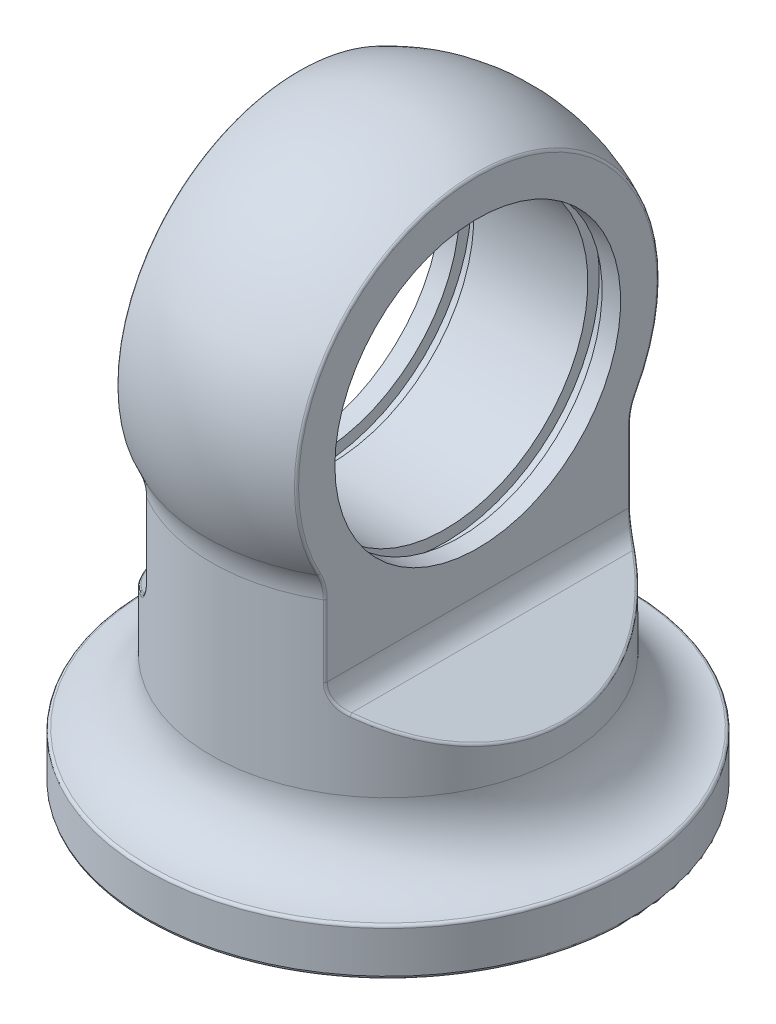
SolidWorks part; units mm, degrees
material "6061-T6 (SS)"
ref_plane "Front Plane" through (0, 0, 0) normal (0, 0, 1) x (1, 0, 0)
ref_plane "Top Plane" through (0, 0, 0) normal (0, 1, 0) x (1, 0, 0)
ref_plane "Right Plane" through (0, 0, 0) normal (1, 0, 0) x (0, 0, -1)
sketch "Sketch11" plane through (0, 0, 0) normal (0, 0, 1) x (1, 0, 0)
  line L0 (0, -7.7453) -> (0, 14.6095) construction
  line L1 (0, 20.32) -> (6.985, 16.123)
  line L2 (6.985, 16.123) -> (6.985, 0)
  line L3 (6.985, 0) -> (21.5138, 0)
  line L4 (21.5138, 0) -> (21.5138, 4.191)
  line L5 (15.748, 9.9568) -> (15.748, 24.8596)
  line L6 (0, 52.832) -> (0, 20.32)
  arc A0 (21.5138, 4.191) -> (15.748, 9.9568) centre (21.5138, 9.9568) cw
  arc A1 (15.748, 24.8596) -> (16.2454, 27.0518) centre (20.828, 24.8596) cw
  arc A2 (16.2454, 27.0518) -> (0, 52.832) centre (0, 34.8234) ccw
  dimension "D1" = 52.832
  dimension "D7" = 36.0172
  dimension "D8" = 5.08
  dimension "D2" = 13.97
  dimension "D3" = 20.32
  dimension "D4" = 59
  dimension "D5" = 31.496
  dimension "D6" = 43.0276
  dimension "D9" = 4.191
revolve "Revolve2" add sketch "Sketch11" angle 360 about L0
sketch "Sketch8" plane through (0, 0, 0) normal (0, 0, 1) x (1, 0, 0)
  line L0 (8.001, 52.832) -> (8.001, 17.018)
  line L1 (8.001, 17.018) -> (18.0086, 11.2401)
  line L2 (0, 62.8796) -> (0, 29.9294) construction
  line L3 (18.0086, 11.2401) -> (18.0086, 52.832)
  line L4 (18.0086, 52.832) -> (8.001, 52.832)
  line L5 (-21.5138, 0) -> (21.5138, 0) construction
  arc A0 (16.2454, 27.0518) -> (-16.2454, 27.0518) centre (0, 34.8234) ccw construction
  dimension "D1" = 16.002
  dimension "D2" = 60
  dimension "D3" = 17.018
extrude "Cut-Extrude1" cut sketch "Sketch8" against normal through all both and the other way through all
mirror "Mirror1" about plane through (0, 0, 0) normal (1, 0, 0) of "Cut-Extrude1"
sketch "Sketch12" plane through (0, 0, 0) normal (0, 0, 1) x (1, 0, 0)
  line L0 (-22.4535, 34.8234) -> (-14.6458, 34.8234) construction
  line L1 (-8.001, 34.8234) -> (-8.001, 47.5615)
  line L2 (-8.001, 50.957) -> (-8.001, 27.0518) construction
  line L3 (-8.001, 47.5615) -> (-6.35, 47.5615)
  line L4 (8.001, 27.0518) -> (8.001, 50.957) construction
  line L5 (8.001, 47.5615) -> (8.001, 34.8234)
  line L6 (8.001, 34.8234) -> (-8.001, 34.8234)
  line L7 (6.35, 47.5615) -> (8.001, 47.5615)
  line L8 (-6.35, 48.5775) -> (-5.08, 48.5775)
  line L9 (-6.35, 48.5775) -> (-6.35, 47.5615)
  line L11 (-5.08, 48.5775) -> (-5.08, 47.5615)
  line L12 (5.08, 48.5775) -> (6.35, 48.5775)
  line L13 (5.08, 48.5775) -> (5.08, 47.5615)
  line L14 (-5.08, 47.5615) -> (5.08, 47.5615)
  line L15 (6.35, 48.5775) -> (6.35, 47.5615)
  dimension "D1" = 25.4762
  dimension "D2" = 10.16
  dimension "D3" = 2.921
  dimension "D4" = 16.002
  dimension "D5" = 1.016
  dimension "D6" = 1.27
ref_point "Point1"
revolve "Cut-Revolve1" cut sketch "Sketch12" angle 360 about L0
fillet "Fillet2" radius 2.54 2 edges at (-8.001, 17.018, 0) (8.001, 17.018, 0)
fillet "Fillet1" radius 0.254 18 edges at (-8.001, 21.672, 13.5641) (-8.001, 21.672, -13.5641) (-8.001, 26.031, -13.7228) (8.001, 21.672, 13.5641) (8.001, 21.672, -13.5641) (8.001, 26.031, -13.7228) (0, 0, -21.5138) (0, 4.191, -21.5138) (-8.001, 50.957, 0) (8.001, 50.957, 0) (-8.4272, 17.0761, 13.3035) (-8.1726, 17.5668, -13.4614) (-15.748, 12.5453, 0) (8.4272, 17.0761, -13.3035) (8.1726, 17.5668, 13.4614) (15.748, 12.5453, 0)
